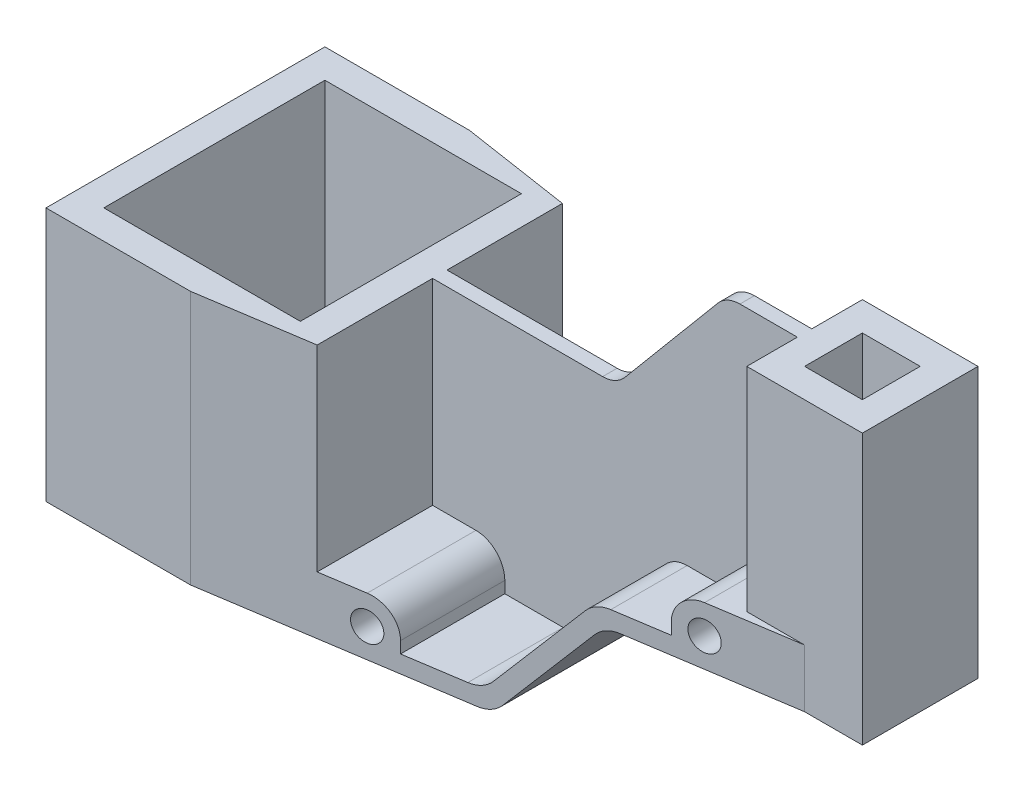
SolidWorks part; units mm, degrees
material "Alliage 1060"
ref_plane "Front Plane" through (0, 0, 0) normal (0, 0, 1) x (1, 0, 0)
ref_plane "Top Plane" through (0, 0, 0) normal (0, 1, 0) x (1, 0, 0)
ref_plane "Right Plane" through (0, 0, 0) normal (1, 0, 0) x (0, 0, -1)
sketch "Esquisse1" plane through (0, 0, 0) normal (0, 1, 0) x (1, 0, 0)
  line L0 (0, 0) -> (251.0912, 0) construction
  line L1 (-44, 48.25) -> (44, 48.25)
  line L2 (-44, 48.25) -> (-44, -48.25)
  line L3 (-44, -48.25) -> (44, -48.25)
  line L4 (44, 48.25) -> (44, -48.25)
  line L10 (-34, 38.25) -> (34, 38.25)
  line L11 (34, 38.25) -> (34, -38.25)
  line L12 (-34, -38.25) -> (34, -38.25)
  line L13 (-34, 38.25) -> (-34, -38.25)
  dimension "D1" = 48.25
  dimension "D2" = 48.25
  dimension "D3" = 88
  dimension "D4" = 44
  dimension "D9" = 10
extrude "Boss.-Extru.3" add sketch "Esquisse1" along normal blind 88
sketch "Esquisse3" plane through (0, 0, 48.25) normal (0, 0, 1) x (1, 0, 0)
  line L0 (44, 0) -> (96.6584, 0)
  line L1 (96.6584, 0) -> (130.2224, 40)
  line L2 (130.2224, 40) -> (190.2224, 40)
  line L3 (44, 6) -> (93.8606, 6)
  line L4 (93.8606, 6) -> (127.4246, 46)
  line L5 (127.4246, 46) -> (190.2224, 46)
  line L6 (190.2224, 46) -> (190.2224, 40)
  dimension "D1" = 6
  dimension "D2" = 130
  dimension "D3" = 40
  dimension "D4" = 60
extrude "Boss.-Extru.4" add sketch "Esquisse3" against normal up to surface (96.5 mm away) contours L6 L5 L4 L3 L0 L1 L2 up to face at (0, 44, -48.25)
sketch "Esquisse7" plane through (0, 40, 0) normal (0, -1, 0) x (1, 0, 0)
  line L0 (0, 0) -> (190.2224, 0) construction
  line L1 (190.2224, -48.25) -> (190.2224, 48.25) construction
  line L2 (180.2224, 10) -> (180.2224, -10)
  line L3 (170.2224, 20) -> (210.2224, 20)
  line L4 (170.2224, 20) -> (170.2224, -20)
  line L5 (170.2224, -20) -> (210.2224, -20)
  line L6 (210.2224, 20) -> (210.2224, -20)
  line L7 (170.2224, 20) -> (210.2224, -20) construction
  line L8 (170.2224, -20) -> (210.2224, 20) construction
  line L9 (180.2224, -10) -> (200.2224, -10)
  line L10 (200.2224, 10) -> (200.2224, -10)
  line L11 (180.2224, 10) -> (200.2224, 10)
  dimension "D1" = 40
  dimension "D2" = 40
  dimension "D3" = 10
extrude "Boss.-Extru.11" add sketch "Esquisse7" against normal blind 93.5
sketch "Esquisse13" plane through (0, 46, 0) normal (0, 1, 0) x (1, 0, 0)
  line L4 (180.2224, -10) -> (190.2224, -10)
  line L21 (180.2224, -10) -> (190.2224, -10)
  line L26 (190.2224, -10) -> (190.2224, 10)
  line L28 (190.2224, -10) -> (190.2224, 10)
  line L30 (190.2224, 10) -> (180.2224, 10)
  line L31 (190.2224, 10) -> (180.2224, 10)
  line L32 (180.2224, 10) -> (180.2224, -10)
  line L33 (180.2224, 10) -> (180.2224, -10)
  dimension "D1" = 0
extrude "Enlèv. mat.-Extru.9" cut sketch "Esquisse13" against normal up to next
sketch "Esquisse14" plane through (0, 0, 0) normal (0, 0, 1) x (1, 0, 0)
  line L0 (44, 88) -> (107.5133, 88)
  line L1 (107.5133, 88) -> (145.6923, 133.5)
  line L2 (145.6923, 133.5) -> (170.2224, 133.5)
  line L8 (93.8606, 6) -> (127.4246, 46) construction
  line L9 (44, 6) -> (93.8606, 6) construction
  line L10 (127.4246, 46) -> (170.2224, 46)
  line L15 (93.8606, 6) -> (127.4246, 46)
  line L16 (44, 6) -> (93.8606, 6)
  line L17 (170.2224, 46) -> (170.2224, 133.5)
  line L18 (44, 88) -> (44, 6)
  dimension "D1" = 42.25
extrude "Boss.-Extru.12" add sketch "Esquisse14" along normal mid plane 5
sketch "Esquisse17" plane through (0, 0, 0) normal (0, 0, 1) x (1, 0, 0)
  line L0 (-44, 88) -> (-44, 0) construction
  line L1 (-44, 0) -> (96.6584, 0) construction
  line L2 (210.2224, 133.5) -> (210.2224, 40) construction
  line L3 (130.2224, 40) -> (190.2224, 40) construction
  line L7 (44, 20) -> (44, 0)
  line L8 (44, 0) -> (69, 0)
  line L9 (69, 0) -> (69, 6)
  line L15 (190.2224, 40) -> (150.2224, 40)
  line L30 (44, 6) -> (93.8606, 6) construction
  line L36 (190.2224, 40) -> (190.2224, 60)
  line L37 (190.2224, 60) -> (150.2224, 60)
  line L38 (150.2224, 40) -> (150.2224, 60)
  line L39 (44, 20) -> (69, 20)
  line L42 (69, 20) -> (69, 6)
  circle A0 centre (59, 10) radius 5
  circle A1 centre (160.2224, 50) radius 5
  dimension "D9" = 10
  dimension "D2" = 10
  dimension "D3" = 103
  dimension "D4" = 10
  dimension "D5" = 50
  dimension "D6" = 10
  dimension "D7" = 10
  dimension "D8" = 10
  dimension "D10" = 20
extrude "Boss.-Extru.13" add sketch "Esquisse17" along normal mid plane 96.5
sketch "Esquisse18" plane through (0, 0, 2.5) normal (0, 0, 1) x (1, 0, 0)
  circle A1 centre (160.2224, 50) radius 5
  circle A2 centre (160.2224, 50) radius 5
  circle A3 centre (59, 10) radius 5
  circle A4 centre (59, 10) radius 5
  dimension "D1" = 0
  dimension "D2" = 0
extrude "Enlèv. mat.-Extru.12" cut sketch "Esquisse18" against normal through all both and the other way through all
sketch "Esquisse19" plane through (0, 60, 0) normal (0, 1, 0) x (1, 0, 0)
  line L4 (180.2224, 10) -> (180.2224, -10)
  line L5 (180.2224, -10) -> (190.2224, -10)
  line L6 (190.2224, -10) -> (190.2224, 10)
  line L7 (190.2224, 10) -> (180.2224, 10)
  line L8 (180.2224, 10) -> (180.2224, -10)
  line L9 (180.2224, -10) -> (190.2224, -10)
  line L10 (190.2224, -10) -> (190.2224, 10)
  line L11 (190.2224, 10) -> (180.2224, 10)
  dimension "D1" = 0
extrude "Enlèv. mat.-Extru.13" cut sketch "Esquisse19" against normal up to next
sketch "Esquisse20" plane through (0, 0, 0) normal (0, 1, 0) x (1, 0, 0)
  line L1 (44, 48.25) -> (-44, 48.25) construction
  line L2 (6, 48.25) -> (190.2224, 20)
  line L3 (170.2224, 20) -> (210.2224, 20) construction
  line L4 (190.2224, 20) -> (210.2224, 20)
  line L6 (210.2224, -20) -> (190.2224, -20)
  line L7 (190.2224, -20) -> (6, -48.25)
  line L8 (6, 48.25) -> (210.2224, 48.25)
  line L9 (210.2224, 48.25) -> (210.2224, 20)
  line L11 (6, -48.25) -> (210.2224, -48.25)
  line L12 (210.2224, -48.25) -> (210.2224, -20)
  line L13 (-44, -48.25) -> (44, -48.25) construction
  point P1 (0, 0)
  point P14 (0, 0)
fillet "Congé1" radius 10 12 edges at (69, 20, -25.375) (93.8606, 6, -25.375) (127.4246, 46, -25.375) (150.2224, 60, -25.375) (96.6584, 0, 0) (130.2224, 40, 0) (150.2224, 60, 25.375) (69, 20, 25.375) (93.8606, 6, 25.375) (127.4246, 46, 25.375) (145.6923, 133.5, 0) (107.5133, 88, 0)
extrude "Enlèv. mat.-Extru.15" cut sketch "Esquisse20" along normal up to surface (133.5 mm away)
equation "\"A\" = 193'a"
equation "\"B\"= 88'b"
equation "\"W\"= \"B\" / 2'w"
equation "\"X\"= \"A\" / 4'x"
equation "\"Y\"= \"B\" + 5.5'y"
equation "\"Z\"= \"B\" + 15'z"
equation "\"C\"= 40"
equation "\"D1@Esquisse1\"=\"X\""
equation "\"D2@Esquisse1\"=\"X\""
equation "\"D3@Esquisse1\"=\"B\""
equation "\"D4@Esquisse1\"=\"W\""
equation "\"D1@Boss.-Extru.11\"=\"Y\""
equation "\"D1@Esquisse14\"=\"X\"-6"
equation "\"D3@Esquisse17\"=\"Z\""
equation "\"D1@Boss.-Extru.13\"=\"X\"*2"
equation "\"D1@Enlèv. mat.-Extru.12\"=\"X\"+\"X\""
